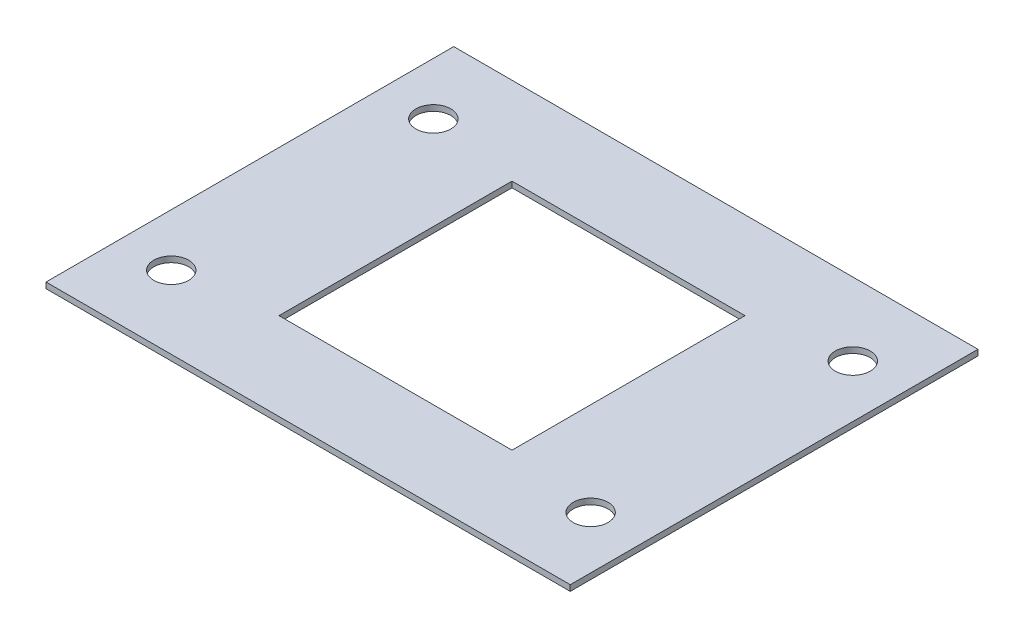
SolidWorks part; units mm, degrees
ref_plane "Alzado" through (0, 0, 0) normal (0, 0, 1) x (1, 0, 0)
ref_plane "Planta" through (0, 0, 0) normal (0, 1, 0) x (1, 0, 0)
ref_plane "Vista lateral" through (0, 0, 0) normal (1, 0, 0) x (0, 0, -1)
sketch "Croquis1" plane through (0, 0, 0) normal (0, 1, 0) x (1, 0, 0)
  line L0 (0, 0) -> (20, 20) construction
  line L1 (0, 0) -> (20, 0)
  line L2 (0, 0) -> (0, 20)
  line L3 (0, 20) -> (20, 20)
  line L4 (20, 0) -> (20, 20)
  line L5 (-12.5, -12.5) -> (32.5, -12.5)
  line L6 (-12.5, -12.5) -> (-12.5, 32.5)
  line L7 (-12.5, 32.5) -> (32.5, 32.5)
  line L8 (32.5, -12.5) -> (32.5, 32.5)
  line L9 (-12.5, 32.5) -> (32.5, -12.5) construction
  line L10 (-14.9749, 34.9749) -> (-12.5, 32.5) construction
  line L11 (28, 10) -> (32.5, 10) construction
  line L12 (10, 10) -> (10, -17.4738) construction
  line L13 (10, 10) -> (0, 10) construction
  line L14 (10, 25) -> (10, 32.5) construction
  line L15 (-5, 25) -> (25, 25) construction
  line L16 (-5, 25) -> (-5, -5) construction
  line L17 (-5, -5) -> (25, -5) construction
  line L18 (25, 25) -> (25, -5) construction
  line L19 (-5, 25) -> (25, -5) construction
  line L20 (-5, -5) -> (25, 25) construction
  line L21 (28, -1.25) -> (28, 10) construction
  line L22 (28, 10) -> (28, 21.25) construction
  line L23 (3, 27.5) -> (10, 27.5) construction
  line L24 (10, 27.5) -> (17, 27.5) construction
  circle A4 centre (-8, 21.25) radius 1.5
  circle A5 centre (-8, -1.25) radius 1.5
  arc A12 (-12.5, -12.3985) -> (-12.3985, -12.5) centre (-9.9749, -9.9749) ccw
  circle A23 centre (28, 21.25) radius 1.5
  circle A24 centre (28, -1.25) radius 1.5
  point P9 (10, 10)
  point P10 (10, 10)
  dimension "D3" = 18
  dimension "D9" = 3
  dimension "D1" = 20
  dimension "D2" = 45
  dimension "D5" = 3.5
  dimension "D6" = 7
  dimension "D8" = 30
  dimension "D10" = 11.25
  dimension "D7" = 17.5
extrude "Saliente-Extruir1" add sketch "Croquis1" along normal blind 0.5
sketch "Croquis2" plane through (0, 0.5, 0) normal (0, 1, 0) x (1, 0, 0)
  line L0 (32.5, -12.5) -> (32.5, 32.5) construction
  line L1 (-12.5, 32.5) -> (32.5, 32.5)
  line L2 (-12.5, 32.5) -> (-12.5, 27.5)
  line L3 (-12.5, 27.5) -> (32.5, 27.5)
  line L4 (32.5, 32.5) -> (32.5, 27.5)
  line L5 (-12.5, -12.3985) -> (-12.5, 32.5) construction
  line L10 (32.5, -12.5) -> (-12.5, -12.5)
  line L11 (32.5, -12.5) -> (32.5, -7.5)
  line L12 (32.5, -7.5) -> (-12.5, -7.5)
  line L13 (-12.5, -12.5) -> (-12.5, -7.5)
  dimension "D1" = 5
extrude "Cortar-Extruir1" cut sketch "Croquis2" against normal blind 10
